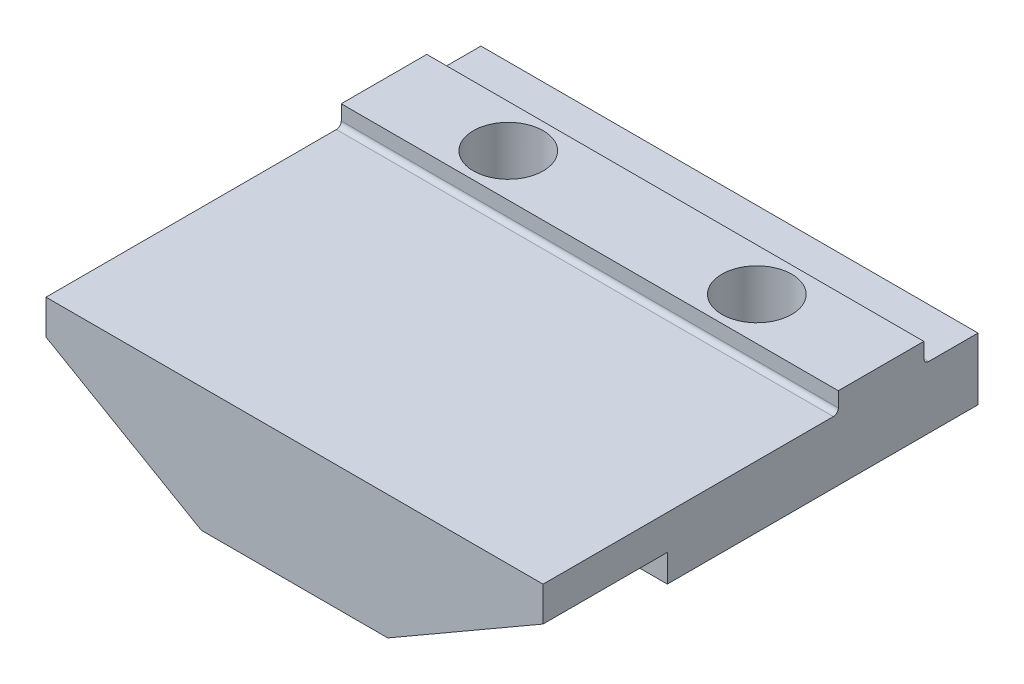
SolidWorks part; units mm, degrees
ref_plane "Front Plane" through (0, 0, 0) normal (0, 0, 1) x (1, 0, 0)
ref_plane "Top Plane" through (0, 0, 0) normal (0, 1, 0) x (1, 0, 0)
ref_plane "Right Plane" through (0, 0, 0) normal (1, 0, 0) x (0, 0, -1)
sketch "Sketch1" plane through (0, 0, 0) normal (0, 1, 0) x (1, 0, 0)
  line L1 (-25.4, -22.225) -> (25.4, -22.225)
  line L2 (-25.4, -22.225) -> (-25.4, 22.225)
  line L3 (-25.4, 22.225) -> (25.4, 22.225)
  line L4 (25.4, -22.225) -> (25.4, 22.225)
  line L5 (-25.4, -22.225) -> (25.4, 22.225) construction
  line L6 (-25.4, 22.225) -> (25.4, -22.225) construction
  point P0 (0, 0)
  dimension "D1" = 25.4
  dimension "D2" = 22.225
extrude "Boss-Extrude1" add sketch "Sketch1" along normal mid plane 6.35
sketch "Sketch2" plane through (0, 0, 0) normal (0, 1, 0) x (1, 0, 0)
  line L1 (-25.4, -22.225) -> (25.4, -22.225)
  line L2 (-25.4, -22.225) -> (-25.4, -9.525)
  line L3 (-25.4, -9.525) -> (25.4, -9.525)
  line L4 (25.4, -22.225) -> (25.4, -9.525)
  point P10 (0, 0)
  dimension "D1" = 50.8
  dimension "D2" = 12.7
  dimension "D3" = 25.4
  dimension "D4" = 22.225
extrude "Boss-Extrude2" add sketch "Sketch2" against normal blind 6.35 from offset 3.175
sketch "Sketch3" plane through (0, 0, 0) normal (0, 1, 0) x (1, 0, 0)
  line L1 (-25.4, 7.9502) -> (25.4, 7.9502)
  line L2 (-25.4, 7.9502) -> (-25.4, 16.6878)
  line L3 (-25.4, 16.6878) -> (25.4, 16.6878)
  line L4 (25.4, 7.9502) -> (25.4, 16.6878)
  point P10 (0, 0)
  dimension "D1" = 50.8
  dimension "D2" = 8.7376
  dimension "D3" = 25.4
  dimension "D4" = 16.6878
extrude "Boss-Extrude3" add sketch "Sketch3" along normal blind 2.032 from offset 3.175
sketch "Sketch4" plane through (0, 0, 0) normal (0, 0, 1) x (1, 0, 0)
  line L0 (-76.2, -22.225) -> (-9.525, -22.225)
  line L1 (-9.525, -22.225) -> (-9.525, -9.525)
  line L2 (-9.525, -9.525) -> (-76.2, 28.9698)
  line L3 (-76.2, 28.9698) -> (-76.2, -22.225)
  point P4 (0, 0)
  dimension "D1" = 66.675
  dimension "D2" = 12.7
  dimension "D3" = 51.1948
  dimension "D4" = 76.2
  dimension "D5" = 22.225
extrude "Cut-Extrude2" cut sketch "Sketch4" against normal blind 12.7 from offset 22.225
sketch "Sketch5" plane through (0, 0, 0) normal (0, 0, 1) x (1, 0, 0)
  line L0 (9.525, -22.225) -> (76.2, -22.225)
  line L1 (76.2, -22.225) -> (76.2, 28.9698)
  line L2 (76.2, 28.9698) -> (9.525, -9.525)
  line L3 (9.525, -9.525) -> (9.525, -22.225)
  point P4 (0, 0)
  dimension "D1" = 66.675
  dimension "D2" = 12.7
  dimension "D3" = 51.1948
  dimension "D4" = 76.2
  dimension "D5" = 22.225
extrude "Cut-Extrude4" cut sketch "Sketch5" against normal blind 12.7 from offset 22.225
sketch "Sketch6" plane through (0, 0, 0) normal (0, 1, 0) x (1, 0, 0)
  circle A0 centre (-12.7, 12.319) radius 3.5687
  circle A1 centre (12.7, 12.319) radius 3.5687
  point P4 (0, 0)
  dimension "D1" = 7.1374
  dimension "D2" = 7.1374
  dimension "D3" = 25.4
  dimension "D4" = 12.7
  dimension "D5" = 12.319
extrude "Cut-Extrude6" cut sketch "Sketch6" against normal blind 9.525 from offset 5.207
fillet "Fillet1" radius 0.508 2 edges at (0, 3.175, -7.9502) (0, 3.175, -16.6878)
